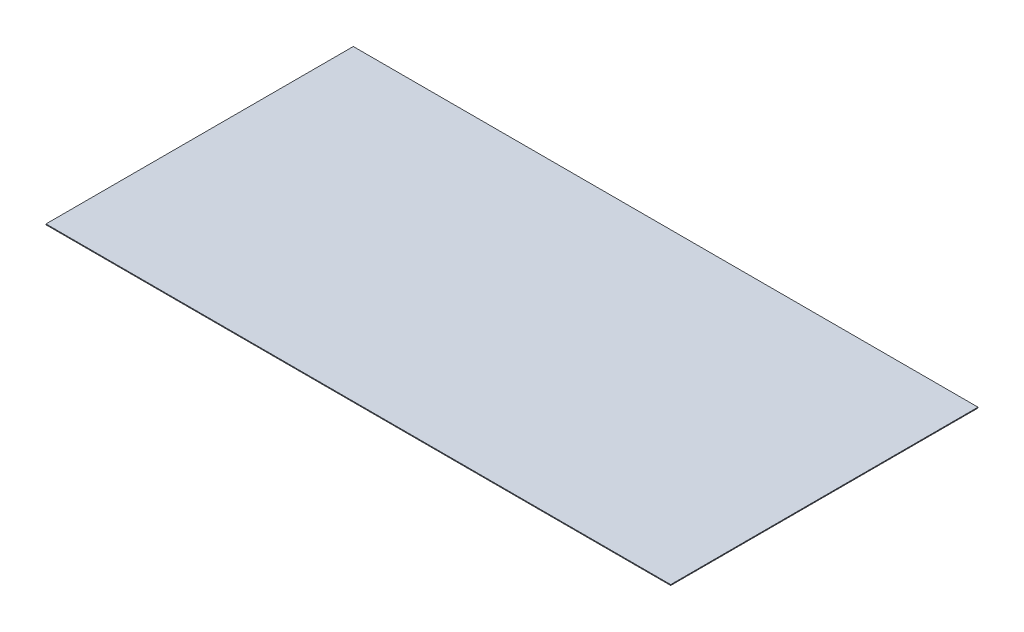
SolidWorks part; units mm, degrees
ref_plane "Płaszczyzna przednia" through (0, 0, 0) normal (0, 0, 1) x (1, 0, 0)
ref_plane "Płaszczyzna górna" through (0, 0, 0) normal (0, 1, 0) x (1, 0, 0)
ref_plane "Płaszczyzna prawa" through (0, 0, 0) normal (1, 0, 0) x (0, 0, -1)
sketch "Szkic1" plane through (0, 0, 0) normal (0, 1, 0) x (1, 0, 0)
  line L1 (-597.5371, -363.7915) -> (947.4629, -363.7915)
  line L2 (-597.5371, -363.7915) -> (-597.5371, 396.2085)
  line L3 (-597.5371, 396.2085) -> (947.4629, 396.2085)
  line L4 (947.4629, -363.7915) -> (947.4629, 396.2085)
  dimension "D1" = 760
  dimension "D2" = 1545
extrude "Dodanie-wyciągnięcie1" add sketch "Szkic1" along normal blind 2
